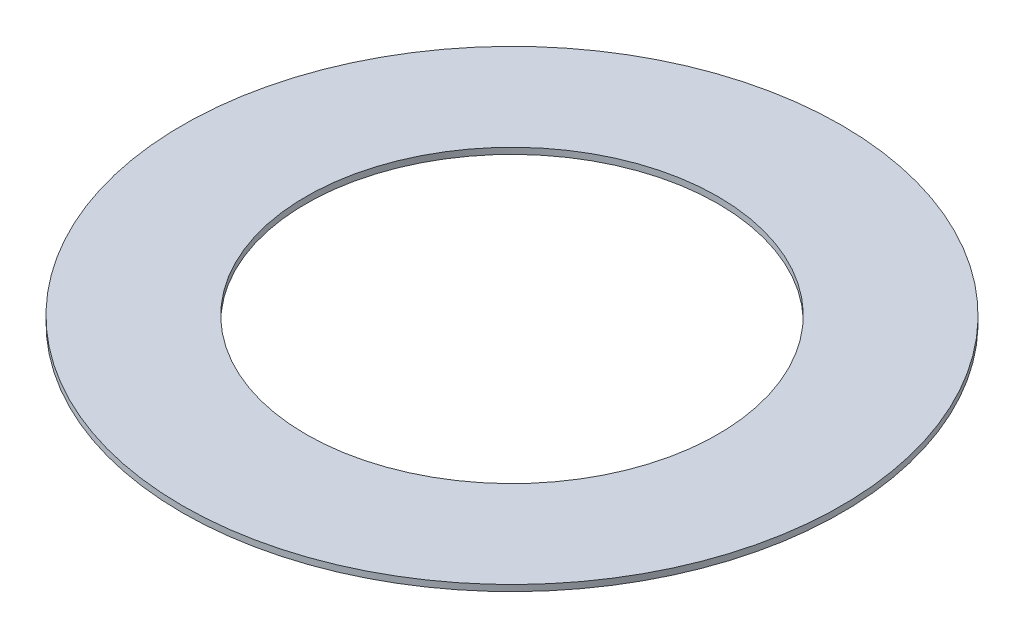
SolidWorks part; units mm, degrees
ref_plane "前视基准面" through (0, 0, 0) normal (0, 0, 1) x (1, 0, 0)
ref_plane "上视基准面" through (0, 0, 0) normal (0, 1, 0) x (1, 0, 0)
ref_plane "右视基准面" through (0, 0, 0) normal (1, 0, 0) x (0, 0, -1)
other "Configuration Table"
sketch "草图1" plane through (0, 0, 0) normal (0, 1, 0) x (1, 0, 0)
  circle A0 centre (0, 0) radius 50
  circle A1 centre (0, 0) radius 80
  dimension "D1" = 100
  dimension "D2" = 160
extrude "凸台-拉伸1" add sketch "草图1" along normal blind 1.5
